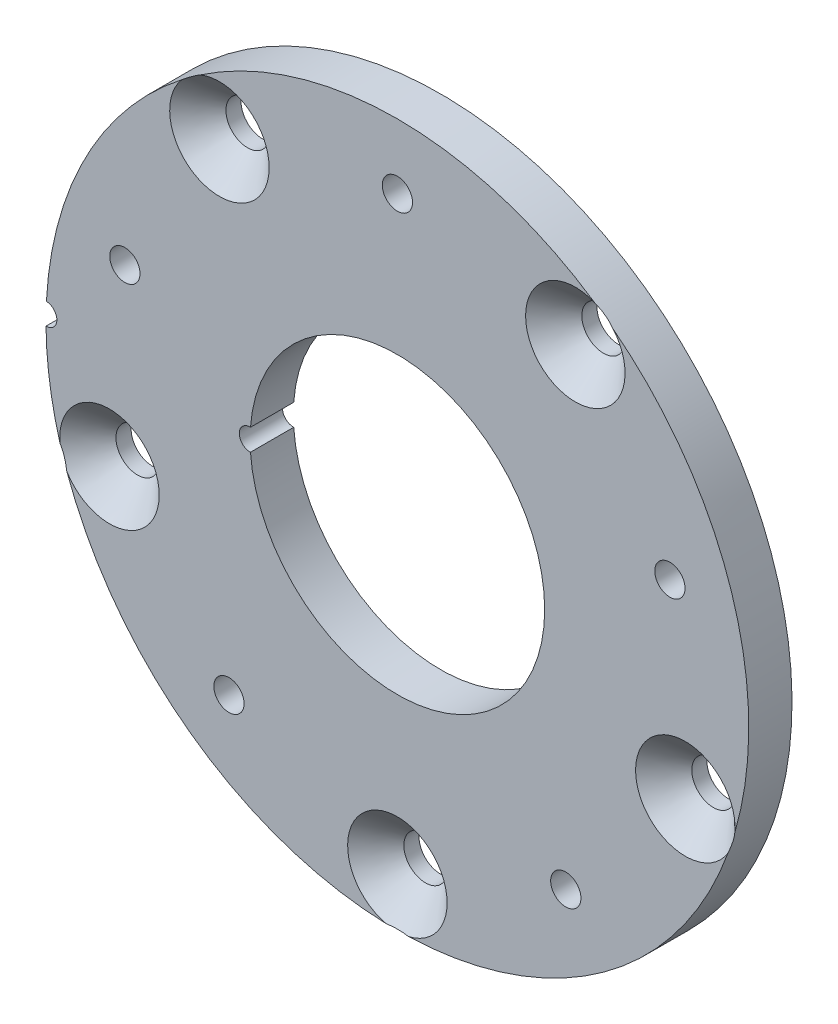
SolidWorks part; units mm, degrees
ref_plane "前视基准面" through (0, 0, 0) normal (0, 0, 1) x (1, 0, 0)
ref_plane "上视基准面" through (0, 0, 0) normal (0, 1, 0) x (1, 0, 0)
ref_plane "右视基准面" through (0, 0, 0) normal (1, 0, 0) x (0, 0, -1)
sketch "草图1" plane through (0, 0, 0) normal (0, 0, 1) x (1, 0, 0)
  line L0 (-26.6296, -8.6525) -> (0, -28) construction
  line L1 (-13.3148, -18.3262) -> (-4.9931, -6.8724) construction
  circle A0 centre (0, 0) radius 32.5
  circle A1 centre (0, 0) radius 13.625
  circle A2 centre (0, -28) radius 2
  circle A3 centre (-26.6296, -8.6525) radius 2
  circle A4 centre (-16.458, 22.6525) radius 2
  circle A5 centre (16.458, 22.6525) radius 2
  circle A6 centre (26.6296, -8.6525) radius 2
  circle A7 centre (0, 0) radius 26.5 construction
  circle A8 centre (-15.5763, -21.439) radius 1.4
  circle A9 centre (-25.203, 8.189) radius 1.4
  circle A10 centre (0, 26.5) radius 1.4
  circle A11 centre (25.203, 8.189) radius 1.4
  circle A12 centre (15.5763, -21.439) radius 1.4
  circle A13 centre (0, 0) radius 28 construction
  dimension "D1" = 65
  dimension "D2" = 53
  dimension "D3" = 27.25
  dimension "D4" = 2.8
  dimension "D6" = 56
  dimension "D5" = 5
extrude "凸台-拉伸1" add sketch "草图1" along normal blind 4 contours A0
sketch "草图2" plane through (0, 0, 4) normal (0, 0, 1) x (1, 0, 0)
  circle A0 centre (-13.625, 0) radius 1
  circle A1 centre (0, 0) radius 13.625 construction
  circle A2 centre (-32.4935, 0.6476) radius 1
  circle A3 centre (0, 0) radius 32.5 construction
  circle A4 centre (-0.2492, 13.6227) radius 1 construction
extrude "切除-拉伸1" cut sketch "草图2" against normal blind 10
ref_point "点1"
sketch "草图5" plane through (0, 0, 0) normal (1, 0, 0) x (0, 0, -1)
  line L0 (-4, -28) -> (-1.4, -28)
  line L1 (-1.4, -28) -> (-1.4, -30)
  line L3 (-4, -28) -> (-4, -32.6)
  line L4 (-4, -32.6) -> (-1.4, -30)
revolve "切除-旋转2" cut sketch "草图5" angle 360 about L0
pattern_circular "阵列(圆周)1" count 5 every 72 about axis through (0, 0, 0) along (0, 0, 1) of "切除-旋转2"
